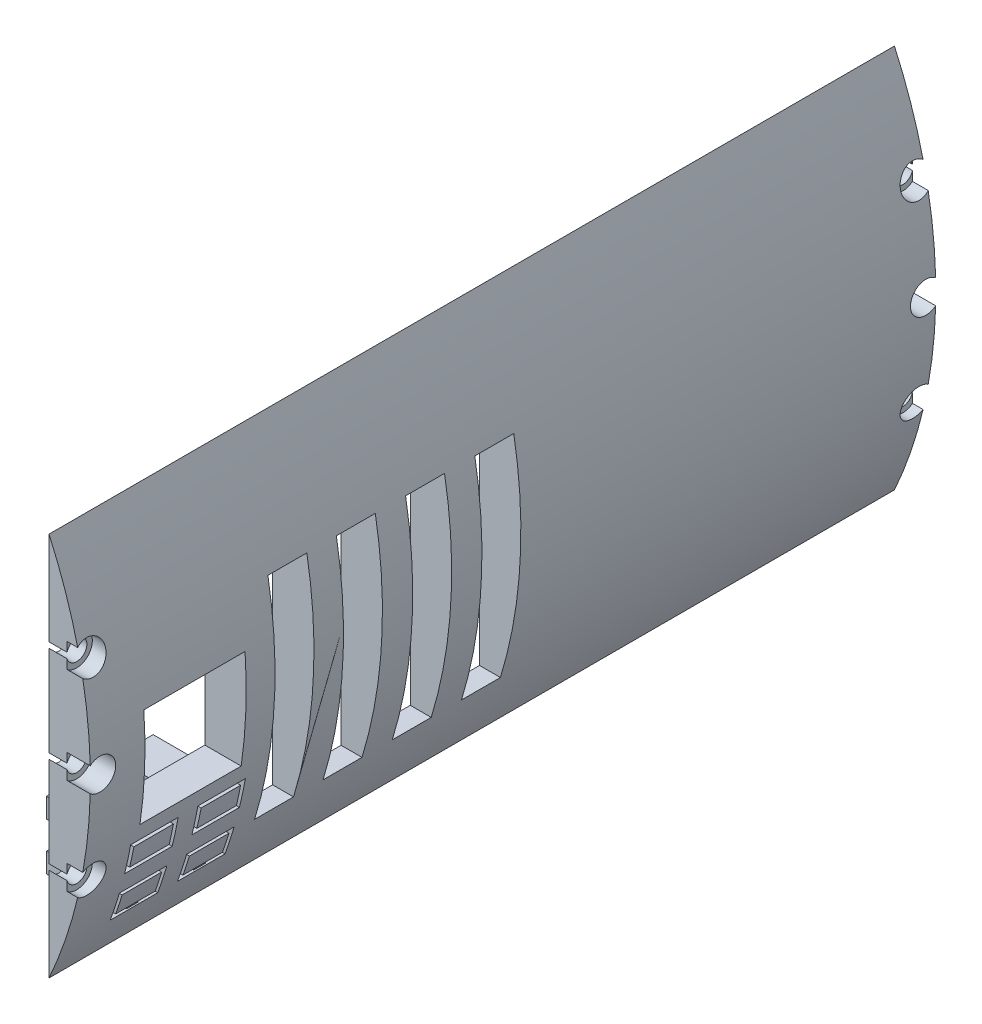
SolidWorks part; units mm, degrees
ref_plane "前视基准面" through (0, 0, 0) normal (0, 0, 1) x (1, 0, 0)
ref_plane "上视基准面" through (0, 0, 0) normal (0, 1, 0) x (1, 0, 0)
ref_plane "右视基准面" through (0, 0, 0) normal (1, 0, 0) x (0, 0, -1)
sketch "草图2" plane through (0, 0, 0) normal (0, 0, 1) x (1, 0, 0)
  line L0 (-18.6863, -24.6863) -> (-18.6863, 24.6863)
  line L1 (-18.6863, 24.6863) -> (-20.6863, 22.5)
  line L2 (-20.6863, 22.5) -> (-20.6863, -22.5)
  line L3 (-20.6863, -22.5) -> (-18.6863, -24.6863)
  line L4 (13.6863, 22.979) -> (24.6863, 22.979)
  line L5 (17.2863, 22.979) -> (17.2863, -23.106)
  line L6 (13.6863, -23.106) -> (24.6863, -23.106)
  line L7 (20.6863, -23.106) -> (20.6863, 22.979)
  line L8 (24.6863, 24.6863) -> (24.6863, -24.6863) construction
  line L9 (-13.496, 11.8369) -> (-13.496, 12.8619) construction
  line L10 (-7.5848, 7.122) -> (-8.6028, 7.122) construction
  line L11 (-8.6869, 9.122) -> (-7.6512, 9.122) construction
  line L12 (-13.496, -16.9434) -> (-13.496, -15.9184) construction
  line L13 (2.6789, -10.6646) -> (3.73, -10.6646) construction
  line L14 (6.5171, -16.946) -> (6.5171, -15.9216) construction
  line L15 (-8.7583, -10.6646) -> (-7.7073, -10.6646) construction
  line L16 (-13.496, 3.0566) -> (-13.496, 4.0816) construction
  line L17 (-11.496, 4.091) -> (-11.496, 3.064) construction
  line L18 (-11.496, -7.1455) -> (-11.496, -8.1725) construction
  line L19 (6.5171, 11.8402) -> (6.5171, 12.8645) construction
  line L20 (3.5348, -12.6646) -> (2.5249, -12.6646) construction
  line L21 (-11.496, -15.909) -> (-11.496, -16.936) construction
  line L22 (11.6863, -25.106) -> (18.0922, -25.106) construction
  line L23 (8.5171, -15.9055) -> (8.5171, -16.9332) construction
  line L24 (-11.496, 12.8545) -> (-11.496, 11.8275) construction
  line L25 (8.5171, 12.8518) -> (8.5171, 11.8241) construction
  line L26 (-16.6863, -25.5479) -> (-16.6863, 25.5479) construction
  line L27 (-13.496, -8.1631) -> (-13.496, -7.1381) construction
  line L28 (8.5171, -7.1482) -> (8.5171, -8.1759) construction
  line L29 (6.5171, -8.1598) -> (6.5171, -7.1355) construction
  line L30 (6.5171, 3.054) -> (6.5171, 4.0784) construction
  line L31 (3.5744, 7.122) -> (2.5564, 7.122) construction
  line L32 (8.5171, 4.0945) -> (8.5171, 3.0668) construction
  line L33 (11.6863, 24.979) -> (18.4746, 24.979) construction
  line L34 (-7.5533, -12.6646) -> (-8.5631, -12.6646) construction
  line L35 (2.6229, 9.122) -> (3.6585, 9.122) construction
  line L36 (15.2863, 24.979) -> (15.2863, -25.106) construction
  line L37 (11.6863, 24.979) -> (11.6863, -25.106) construction
  line L38 (-24.6863, -24.6863) -> (-24.6863, 24.6863) construction
  line L39 (13.6863, 22.979) -> (13.6863, -23.106) construction
  line L40 (14.6863, -4.612) -> (14.6863, -9.612) construction
  line L41 (14.6863, 13.549) -> (14.6863, 8.549) construction
  line L42 (12.6863, -6.212) -> (12.6863, -8.012) construction
  line L43 (12.6863, 11.949) -> (12.6863, 10.149) construction
  line L44 (-18.6863, -24.6863) -> (-24.6863, -24.6863) construction
  line L45 (-18.6863, 24.6863) -> (-24.6863, 24.6863) construction
  line L46 (14.6863, -13.756) -> (14.6863, -18.756) construction
  line L47 (12.6863, -15.356) -> (12.6863, -17.156) construction
  line L48 (-19.6863, 11.4431) -> (-19.6863, 13.2431) construction
  line L49 (-19.6863, 13.2431) -> (-24.6863, 13.2431) construction
  line L50 (-24.6863, 11.4431) -> (-19.6863, 11.4431) construction
  line L51 (-19.6863, -0.9) -> (-19.6863, 0.9) construction
  line L52 (-19.6863, 0.9) -> (-24.6863, 0.9) construction
  line L53 (-24.6863, -0.9) -> (-19.6863, -0.9) construction
  line L54 (-19.6863, -11.4431) -> (-24.6863, -11.4431) construction
  line L55 (-22.6863, 23.3791) -> (-22.6863, -23.3791) construction
  line L56 (-24.6863, -13.2431) -> (-19.6863, -13.2431) construction
  line L57 (-19.6863, -13.2431) -> (-19.6863, -11.4431) construction
  line L58 (19.6863, -11.4431) -> (19.6863, -13.2431) construction
  line L59 (22.6863, -13.0915) -> (19.6863, -13.0915) construction
  line L60 (19.6863, -11.5948) -> (22.6863, -11.5948) construction
  line L61 (19.6863, 13.2431) -> (19.6863, 11.4431) construction
  line L62 (22.6863, 11.5948) -> (19.6863, 11.5948) construction
  line L63 (19.6863, 13.0915) -> (22.6863, 13.0915) construction
  line L64 (22.6863, -0.7483) -> (19.6863, -0.7483) construction
  line L65 (22.6863, -23.3791) -> (22.6863, 23.3791) construction
  line L66 (19.6863, 0.7483) -> (22.6863, 0.7483) construction
  line L67 (19.6863, 0.9) -> (19.6863, -0.9) construction
  line L68 (-19.0096, -24.5333) -> (-17.553, -22.4531) construction
  line L69 (-15.0955, -24.1738) -> (-16.5521, -26.2541) construction
  line L70 (-16.5521, -26.2541) -> (-19.0096, -24.5333) construction
  line L71 (-26.2541, 16.5521) -> (-24.5333, 19.0096) construction
  line L72 (-24.5333, 19.0096) -> (-22.4531, 17.553) construction
  line L73 (-24.1738, 15.0955) -> (-26.2541, 16.5521) construction
  line L74 (24.5333, -19.0096) -> (22.4531, -17.553) construction
  line L75 (26.2541, -16.5521) -> (24.5333, -19.0096) construction
  line L76 (24.1738, -15.0955) -> (26.2541, -16.5521) construction
  line L77 (15.0955, 24.1738) -> (16.5521, 26.2541) construction
  line L78 (19.0096, 24.5333) -> (17.553, 22.4531) construction
  line L79 (16.5521, 26.2541) -> (19.0096, 24.5333) construction
  line L80 (24.6863, 13.2431) -> (19.6863, 13.2431) construction
  line L81 (19.6863, 11.4431) -> (24.6863, 11.4431) construction
  line L82 (24.6863, 0.9) -> (19.6863, 0.9) construction
  line L83 (19.6863, -0.9) -> (24.6863, -0.9) construction
  line L84 (24.6863, -11.4431) -> (19.6863, -11.4431) construction
  line L85 (19.6863, -13.2431) -> (24.6863, -13.2431) construction
  line L86 (13.6863, -9.612) -> (14.6863, -9.612) construction
  line L87 (14.6863, -4.612) -> (13.6863, -4.612) construction
  line L88 (13.6863, 8.549) -> (14.6863, 8.549) construction
  line L89 (14.6863, 13.549) -> (13.6863, 13.549) construction
  line L90 (14.6863, -6.212) -> (12.6863, -6.212) construction
  line L91 (12.6863, -8.012) -> (14.6863, -8.012) construction
  line L92 (14.6863, 11.949) -> (12.6863, 11.949) construction
  line L93 (12.6863, 10.149) -> (14.6863, 10.149) construction
  line L94 (13.6863, -18.756) -> (14.6863, -18.756) construction
  line L95 (14.6863, -13.756) -> (13.6863, -13.756) construction
  line L96 (14.6863, -15.356) -> (12.6863, -15.356) construction
  line L97 (12.6863, -17.156) -> (14.6863, -17.156) construction
  circle A0 centre (-17.526, -16.002) radius 0.9
  circle A1 centre (4.699, 11.303) radius 2
  circle A2 centre (4.699, 11.303) radius 0.9
  circle A3 centre (6.985, -21.844) radius 2
  circle A4 centre (6.985, -21.844) radius 0.9
  circle A5 centre (0, 0) radius 26.5 construction
  circle A6 centre (0, 0) radius 28.5 construction
  arc A7 (23.1707, 23.1707) -> (-23.1707, 23.1707) centre (0, -30) ccw
  arc A8 (-23.1707, 23.1707) -> (-23.1707, -23.1707) centre (30, 0) ccw
  arc A9 (23.1707, -23.1707) -> (23.1707, 23.1707) centre (-30, 0) ccw
  arc A10 (-24.6863, 24.6863) -> (-24.6863, -24.6863) centre (30, 0) ccw
  arc A11 (24.6863, 24.6863) -> (-24.6863, 24.6863) centre (0, -30) ccw
  arc A12 (-24.6863, -24.6863) -> (24.6863, -24.6863) centre (0, 30) ccw
  arc A13 (24.6863, -24.6863) -> (24.6863, 24.6863) centre (-30, 0) ccw
  arc A14 (-23.1707, -23.1707) -> (23.1707, -23.1707) centre (0, 30) ccw
  arc A15 (-18.6863, -17.631) -> (-18.6863, -14.373) centre (-17.526, -16.002) ccw
  arc A16 (3.5348, -12.6646) -> (6.5171, -15.9216) centre (7.4858, -12.0407) ccw construction
  arc A17 (8.5171, -15.9055) -> (8.5171, -8.1759) centre (7.4858, -12.0407) ccw construction
  arc A18 (6.5171, -8.1598) -> (3.73, -10.6646) centre (7.4858, -12.0407) ccw construction
  arc A19 (-11.496, -16.936) -> (-7.5533, -12.6646) centre (-12.5142, -12.0407) ccw construction
  arc A20 (3.5744, 7.122) -> (6.5171, 4.0784) centre (7.4858, 7.9593) ccw construction
  arc A21 (11.6863, -9.3285) -> (8.5171, -7.1482) centre (7.4858, -12.0407) ccw construction
  arc A22 (8.5171, -16.9332) -> (11.6863, -14.753) centre (7.4858, -12.0407) ccw construction
  arc A23 (6.5171, -7.1355) -> (2.6789, -10.6646) centre (7.4858, -12.0407) ccw construction
  arc A24 (-15.1576, -16.2848) -> (-13.496, -16.9434) centre (-12.5142, -12.0407) ccw construction
  arc A25 (-8.6869, 9.122) -> (-11.496, 11.8275) centre (-12.5142, 7.9593) ccw construction
  arc A26 (-7.6512, 9.122) -> (-11.496, 12.8545) centre (-12.5142, 7.9593) ccw construction
  arc A27 (-11.496, -15.909) -> (-8.5631, -12.6646) centre (-12.5142, -12.0407) ccw construction
  arc A28 (-13.496, -7.1381) -> (-15.1576, -7.7966) centre (-12.5142, -12.0407) ccw construction
  arc A29 (-13.496, -8.1631) -> (-13.496, -15.9184) centre (-12.5142, -12.0407) ccw construction
  arc A30 (8.5171, 4.0945) -> (8.5171, 11.8241) centre (7.4858, 7.9593) ccw construction
  arc A31 (6.5171, 11.8402) -> (3.6585, 9.122) centre (7.4858, 7.9593) ccw construction
  arc A32 (11.6863, 10.6715) -> (8.5171, 12.8518) centre (7.4858, 7.9593) ccw construction
  arc A33 (-11.496, 4.091) -> (-8.6028, 7.122) centre (-12.5142, 7.9593) ccw construction
  arc A34 (-13.496, 12.8619) -> (-15.1576, 12.2034) centre (-12.5142, 7.9593) ccw construction
  arc A35 (-8.7583, -10.6646) -> (-11.496, -8.1725) centre (-12.5142, -12.0407) ccw construction
  arc A36 (-11.496, 3.064) -> (-7.5848, 7.122) centre (-12.5142, 7.9593) ccw construction
  arc A37 (-7.7073, -10.6646) -> (-11.496, -7.1455) centre (-12.5142, -12.0407) ccw construction
  arc A38 (2.5249, -12.6646) -> (6.5171, -16.946) centre (7.4858, -12.0407) ccw construction
  arc A39 (6.5171, 12.8645) -> (2.6229, 9.122) centre (7.4858, 7.9593) ccw construction
  arc A40 (8.5171, 3.0668) -> (11.6863, 5.247) centre (7.4858, 7.9593) ccw construction
  arc A41 (-15.1576, 3.7152) -> (-13.496, 3.0566) centre (-12.5142, 7.9593) ccw construction
  arc A42 (-13.496, 11.8369) -> (-13.496, 4.0816) centre (-12.5142, 7.9593) ccw construction
  arc A43 (2.5564, 7.122) -> (6.5171, 3.054) centre (7.4858, 7.9593) ccw construction
  arc A44 (-16.6863, -6.9478) -> (-15.1576, -7.7966) centre (-15.6863, -6.9478) ccw construction
  arc A45 (-15.1576, 3.7152) -> (-16.6863, 2.8664) centre (-15.6863, 2.8664) ccw construction
  arc A46 (-15.1576, -16.2848) -> (-16.6863, -17.1336) centre (-15.6863, -17.1336) ccw construction
  arc A47 (-16.6863, 13.0522) -> (-15.1576, 12.2034) centre (-15.6863, 13.0522) ccw construction
  arc A48 (11.6863, -17.1159) -> (10.1529, -16.27) centre (10.6863, -17.1159) ccw construction
  arc A49 (10.1529, -7.8114) -> (11.6863, -6.9656) centre (10.6863, -6.9656) ccw construction
  arc A50 (11.6863, 2.8841) -> (10.1529, 3.73) centre (10.6863, 2.8841) ccw construction
  arc A51 (10.1529, 12.1886) -> (11.6863, 13.0344) centre (10.6863, 13.0344) ccw construction
sketch "草图3" plane through (0, 0, 0) normal (0, 0, 1) x (1, 0, 0)
  line L2 (24.6863, 24.6863) -> (24.6863, -24.6863)
  line L3 (24.6863, 24.6863) -> (24.6863, -24.6863)
  arc A3 (24.6863, -24.6863) -> (24.6863, 24.6863) centre (-30, 0) ccw
  arc A4 (24.6863, -24.6863) -> (24.6863, 24.6863) centre (-30, 0) ccw
  dimension "D1" = 0
extrude "凸台-拉伸1" add sketch "草图3" along normal blind 108.58
sketch "草图4" plane through (24.6863, 0, 0) normal (-1, 0, 0) x (0, 0, 1)
  point P0 (0, 0.001)
  point P1 (0.001, 0.001)
  point P2 (0.001, 0)
sketch "草图8" plane through (24.6863, 0, 0) normal (-1, 0, 0) x (0, 0, 1)
  line L0 (108.58, 24.6863) -> (108.58, -24.6863) construction
  line L1 (108.58, 24.6863) -> (0, 24.6863) construction
  line B0 (108.83, -24.6863) -> (108.83, 24.6863)
  line B1 (120.832, 24.6863) -> (-9.168, 24.6863)
  line B2 (2.754, 23.106) -> (2.754, -22.979)
  line B3 (2.754, -22.979) -> (104.83, -22.979)
  line B4 (104.83, 23.106) -> (2.754, 23.106)
  line B5 (104.83, -22.979) -> (104.83, 23.106)
  circle B6 centre (107.33, 12.3431) radius 0.9
  line B7 (120.832, 30) -> (-9.168, 30)
  circle B8 centre (17.454, 16.256) radius 2.5
  circle B9 centre (1.254, 12.3431) radius 0.9
  line B10 (-0.246, 24.6863) -> (-0.246, -24.6863)
  line B11 (-9.168, -30) -> (-9.168, 30)
  line B12 (-19.168, -28.5) -> (-19.168, 28.5)
  circle B13 centre (1.254, 0) radius 0.9
  circle B14 centre (1.254, -12.3431) radius 0.9
  line B15 (120.832, -30) -> (120.832, 30)
  circle B16 centre (102.036, 7.112) radius 2.5
  circle B17 centre (107.33, 0) radius 0.9
  circle B18 centre (102.036, -11.049) radius 2.5
  circle B19 centre (102.036, -11.049) radius 0.9
  circle B20 centre (107.33, -12.3431) radius 0.9
  circle B21 centre (17.454, 16.256) radius 0.9
  line B22 (-14.168, 15.0955) -> (-14.168, 19.0096)
  line B23 (-14.168, 16.5521) -> (-17.168, 16.5521)
  line B24 (-9.168, -30) -> (120.832, -30)
  line B25 (-9.168, -24.6863) -> (120.832, -24.6863)
  line B26 (-17.168, 15.0955) -> (-17.168, 19.0096)
  line B27 (-17.168, -22.4531) -> (-14.168, -22.4531)
  line B28 (-17.168, -26.2541) -> (-17.168, -22.4531)
  line B29 (-19.168, -28.5) -> (-9.168, -28.5)
  dimension "D1" = 0.25
sketch_block_instance "块1-2"
sketch_block "块1"
ref_plane "基准面5" through (30, 0, 0) normal (1, 0, 0) x (0, 0, -1)
sketch "草图11" plane through (30, 0, 0) normal (1, 0, 0) x (0, 0, -1)
  circle A0 centre (-1.254, -12.3431) radius 2
  circle A1 centre (-1.254, 0) radius 2
  circle A2 centre (-1.254, 12.3431) radius 2
  circle A3 centre (-107.33, -12.3431) radius 2
  circle A4 centre (-107.33, 0) radius 2
  circle A5 centre (-107.33, 12.3431) radius 2
  dimension "D1" = 4
extrude "切除-拉伸4" cut sketch "草图11" against normal blind 3
sketch "草图12" plane through (27, 0, 0) normal (1, 0, 0) x (0, 0, -1)
  circle A0 centre (-1.254, -12.3431) radius 1.3
  circle A1 centre (-1.254, 0) radius 1.3
  circle A2 centre (-1.254, 12.3431) radius 1.3
  circle A3 centre (-107.33, 12.3431) radius 1.3
  circle A4 centre (-107.33, 0) radius 1.3
  circle A5 centre (-107.33, -12.3431) radius 1.3
  dimension "D1" = 2.6
extrude "切除-拉伸5" cut sketch "草图12" against normal blind 14
sketch "草图14" plane through (0, 0, 0) normal (1, 0, 0) x (0, 0, -1)
  arc A0 (-108.58, -12.7002) -> (-108.58, -11.9861) centre (-107.33, -12.3431) ccw construction
  arc A1 (0, 12.6859) -> (0, 12.0004) centre (-1.254, 12.3431) ccw construction
  line B0 (-77.5411, 13.97) -> (-77.5411, -21.082) construction
  line B1 (-105.83, 23.106) -> (-105.83, -22.979)
  circle B2 centre (-97.5669, 3.9639) radius 1.2754 construction
  line B3 (-84.907, -13.8431) -> (-84.907, 6.6039) construction
  line B4 (-71.064, 6.6039) -> (-71.064, -13.8431) construction
  line B5 (12.248, 24.6863) -> (-117.752, 24.6863)
  circle B6 centre (-53.8241, 13.1941) radius 0.8163 construction
  circle B7 centre (-57.824, 13.1938) radius 1.2754 construction
  circle B8 centre (-62.714, 13.1938) radius 1.2754 construction
  line B9 (-78.367, -21.082) -> (-78.367, 13.97) construction
  line B10 (-102.56, 11.43) -> (-102.56, 21.59) construction
  line B11 (-87.699, -14.373) -> (-93.799, -14.373) construction
  line B12 (-86.3041, 13.97) -> (-86.3041, -21.082) construction
  line B13 (-79.9541, -11.176) -> (-84.7801, -11.176) construction
  line B14 (-79.827, -13.8431) -> (-84.907, -13.8431) construction
  line B15 (-84.7801, -8.636) -> (-79.9541, -8.636) construction
  line B16 (-79.827, 6.6039) -> (-79.827, -13.8431) construction
  line B17 (-76.144, -13.8431) -> (-76.144, 6.6039) construction
  line B18 (-60.714, -21.082) -> (-60.714, 13.97) construction
  line B19 (-47.3406, -2.1709) -> (-46.0194, -2.1709) construction
  line B20 (-85.161, 20.955) -> (-85.161, 15.875) construction
  line B21 (-85.161, 15.875) -> (-87.6756, 15.875) construction
  circle B22 centre (-92.567, 3.964) radius 0.7653 construction
  circle B23 centre (-95.0667, -2.286) radius 5.9146 construction
  line B24 (-99.0268, 3.714) -> (-101.067, 3.714) construction
  circle B25 centre (-90.5669, -2.286) radius 0.95 construction
  line B26 (-89.067, -5.4368) -> (-89.067, 3.714) construction
  circle B27 centre (-100.1419, 1.5138) radius 0.9254 construction
  circle B28 centre (-100.142, 1.514) radius 0.6169 construction
  circle B29 centre (-89.992, -6.086) radius 0.6169 construction
  line B30 (-89.067, -8.286) -> (-89.067, -6.7352) construction
  circle B31 centre (-84.367, 13.1938) radius 1.2754 construction
  circle B32 centre (-84.367, 13.1941) radius 0.8163 construction
  line B33 (-117.752, -30) -> (-117.752, 30)
  line B34 (-84.907, 6.6039) -> (-79.827, 6.6039) construction
  line B35 (-69.604, -21.082) -> (-69.604, 13.97) construction
  line B36 (-67.254, -13.8431) -> (-67.254, 6.6039) construction
  line B37 (-62.174, 6.6039) -> (-62.174, -13.8431) construction
  circle B38 centre (-55.697, 5.207) radius 0.3048 construction
  line B39 (-58.364, 6.6039) -> (-53.284, 6.6039) construction
  line B40 (-51.824, -21.082) -> (-51.824, 13.97) construction
  line B41 (-53.284, 6.6039) -> (-53.284, -13.8431) construction
  line B42 (-53.4111, -11.176) -> (-58.2371, -11.176) construction
  line B43 (-68.6511, 13.97) -> (-68.6511, -21.082) construction
  line B44 (-93.289, -11.303) -> (-88.209, -11.303) construction
  line B45 (-87.699, -10.773) -> (-93.799, -10.773) construction
  circle B46 centre (-97.5669, -8.5362) radius 1.2754 construction
  line B47 (-100.782, -11.938) -> (-98.115, -11.938) construction
  line B48 (-101.925, -11.8419) -> (-101.925, -11.303) construction
  line B49 (-98.115, -13.208) -> (-100.782, -13.208) construction
  line B50 (-96.845, -13.843) -> (-101.925, -13.843) construction
  line B51 (-93.289, -11.8419) -> (-93.289, -11.303) construction
  line B52 (-92.146, -11.938) -> (-89.479, -11.938) construction
  line B53 (-89.479, -11.938) -> (-89.479, -13.208) construction
  line B54 (-88.209, -13.843) -> (-93.289, -13.843) construction
  line B55 (-87.699, -16.869) -> (-93.799, -16.869) construction
  line B56 (-96.335, -20.469) -> (-96.335, -19.4001) construction
  line B57 (-98.115, -19.304) -> (-100.782, -19.304) construction
  line B58 (-100.782, -18.034) -> (-98.115, -18.034) construction
  line B59 (-101.925, -17.399) -> (-96.845, -17.399) construction
  line B60 (-93.289, -17.399) -> (-88.209, -17.399) construction
  line B61 (-89.479, -19.304) -> (-92.146, -19.304) construction
  line B62 (-88.209, -19.939) -> (-93.289, -19.939) construction
  line B63 (-87.699, -20.469) -> (-93.799, -20.469) construction
  line B64 (-96.335, -10.773) -> (-102.435, -10.773) construction
  line B65 (-103.83, -22.479) -> (-103.83, 22.606) construction
  circle B66 centre (-46.172, -18.796) radius 3.1496 construction
  line B67 (-117.752, -24.6863) -> (12.248, -24.6863)
  line B68 (-117.752, -30) -> (12.248, -30)
  line B69 (-87.2944, -8.1161) -> (-88.6156, -8.1161) construction
  line B70 (-88.2908, -8.6104) -> (-87.3319, -8.6104) construction
  circle B71 centre (-87.9636, -9.271) radius 0.3048 construction
  circle B72 centre (-97.567, 3.964) radius 0.75 construction
  line B73 (-101.067, 0.8648) -> (-101.067, -8.286) construction
  spline B74 degree 3 poles (-108.83, -1.3229) (-108.9908, -1.1406) (-109.1152, -0.9337) (-109.2436, -0.5939) (-109.2757, -0.4783) (-109.3189, -0.2424) (-109.33, -0.121) (-109.33, 0.1204) (-109.3192, 0.2398) (-109.2762, 0.476) (-109.2436, 0.5939) (-109.116, 0.9318) (-108.9908, 1.1406) (-108.83, 1.3229) knots 0 0 0 0 0.25 0.25 0.375 0.375 0.5 0.5 0.625 0.625 0.75 0.75 1 1 1 1
  line B75 (-108.83, 24.6863) -> (-108.83, -24.6863)
  line B76 (-71.064, -13.8431) -> (-76.144, -13.8431) construction
  circle B77 centre (-80.367, 13.1938) radius 1.2754 construction
  circle B78 centre (-98.75, 12.7) radius 0.8128 construction
  line B79 (-51.824, 13.97) -> (-59.7611, 13.97) construction
  circle B80 centre (-53.824, 13.1938) radius 1.2754 construction
  circle B81 centre (-91.13, 16.256) radius 1.5999 construction
  line B82 (-59.7611, 13.97) -> (-59.7611, -21.082) construction
  circle B83 centre (-71.604, 13.1938) radius 1.2754 construction
  circle B84 centre (-75.604, 13.1938) radius 1.2754 construction
  line B85 (-100.02, 11.43) -> (-100.02, 19.685) construction
  circle B86 centre (-101.29, 15.24) radius 0.8128 construction
  circle B87 centre (-101.29, 12.7) radius 0.4588 construction
  circle B88 centre (-80.3671, 13.1941) radius 0.8163 construction
  line B89 (-78.367, 13.97) -> (-86.3041, 13.97) construction
  line B90 (-105.83, -22.979) -> (-3.754, -22.979)
  line B91 (-3.754, -22.479) -> (-103.754, -22.479) construction
  line B92 (-78.367, -21.082) -> (-86.367, -21.082) construction
  circle B93 centre (-84.145, -14.351) radius 0.3048 construction
  line B94 (-127.752, -28.5) -> (-127.752, 28.5)
  line B95 (-71.1911, -11.176) -> (-76.0171, -11.176) construction
  line B96 (-69.604, 13.97) -> (-77.5411, 13.97) construction
  circle B97 centre (-66.714, 13.1938) radius 1.2754 construction
  line B98 (-60.714, 13.97) -> (-68.6511, 13.97) construction
  circle B99 centre (-97.567, 3.964) radius 0.7653 construction
  line B100 (-58.364, -13.8431) -> (-58.364, 6.6039) construction
  line B101 (-57.983, 15.367) -> (-57.983, 21.367) construction
  line B102 (-57.983, 15.367) -> (-52.903, 15.367) construction
  circle B103 centre (-55.697, 18.367) radius 0.9 construction
  line B104 (-50.3972, 9.4917) -> (-44.9948, 9.4917) construction
  circle B105 centre (-40.965, 5.334) radius 0.3048 construction
  circle B106 centre (-87.193, -14.351) radius 0.3048 construction
  line B107 (-62.3011, -11.176) -> (-67.1271, -11.176) construction
  circle B108 centre (-84.367, -20.3062) radius 0.8163 construction
  line B109 (-96.335, -14.373) -> (-102.435, -14.373) construction
  line B110 (-100.782, -13.208) -> (-100.782, -11.938) construction
  circle B111 centre (-107.33, -12.3431) radius 0.9
  line B112 (-96.335, -16.869) -> (-102.435, -16.869) construction
  line B113 (-101.925, -11.303) -> (-96.845, -11.303) construction
  line B114 (-102.435, -11.8419) -> (-102.435, -10.773) construction
  line B115 (-96.335, -14.373) -> (-96.335, -13.3041) construction
  line B116 (-102.435, -17.9379) -> (-102.435, -16.869) construction
  line B117 (-96.335, -20.469) -> (-102.435, -20.469) construction
  line B118 (-101.925, -17.9379) -> (-101.925, -17.399) construction
  line B119 (-96.845, -19.939) -> (-101.925, -19.939) construction
  line B120 (-92.146, -19.304) -> (-92.146, -18.034) construction
  line B121 (-100.782, -19.304) -> (-100.782, -18.034) construction
  circle B122 centre (-92.5669, -8.5362) radius 1.25 construction
  spline B123 degree 3 poles (-108.83, -13.666) (-108.9914, -13.4831) (-109.1153, -13.2765) (-109.2862, -12.8243) (-109.3297, -12.587) (-109.3302, -12.2254) (-109.3195, -12.1063) (-109.277, -11.8705) (-109.2447, -11.7528) (-109.1172, -11.4135) (-108.9922, -11.2042) (-108.83, -11.0203) knots 0 0 0 0 0.25 0.25 0.5 0.5 0.625 0.625 0.75 0.75 1 1 1 1
  circle B124 centre (-92.567, -8.536) radius 0.7653 construction
  circle B125 centre (-97.567, -8.536) radius 0.7653 construction
  line B126 (-89.479, -18.034) -> (-89.479, -19.304) construction
  line B127 (-92.146, -18.034) -> (-89.479, -18.034) construction
  line B128 (-89.479, -13.208) -> (-92.146, -13.208) construction
  line B129 (-98.115, -11.938) -> (-98.115, -13.208) construction
  line B130 (-93.799, -20.469) -> (-93.799, -19.4001) construction
  line B131 (-98.115, -18.034) -> (-98.115, -19.304) construction
  line B132 (-60.714, -21.082) -> (-68.714, -21.082) construction
  circle B133 centre (-66.714, -20.3062) radius 0.8163 construction
  circle B134 centre (-92.5669, -8.5362) radius 1.2754 construction
  line B135 (-92.146, -13.208) -> (-92.146, -11.938) construction
sketch_block_instance "块2-1"
sketch_block "块2"
sketch "草图15" plane through (24.6863, 0, 0) normal (-1, 0, 0) x (0, 0, 1)
  line L0 (95.0667, -2.286) -> (101.5667, -2.286) construction
  line L37 (101.5667, 4.214) -> (88.5667, 4.214)
  line L38 (101.5667, 4.214) -> (101.5667, -8.786)
  line L39 (101.5667, -8.786) -> (88.5667, -8.786)
  line L40 (88.5667, 4.214) -> (88.5667, -8.786)
  line L41 (82.3355, 13.97) -> (82.367, 10.4441) construction
  line L42 (95.0667, -2.286) -> (95.0667, 4.214) construction
  line L47 (84.867, 10.4441) -> (79.867, 10.4441)
  line L48 (84.867, 10.4441) -> (84.867, -17.5559)
  line L49 (84.867, -17.5559) -> (79.867, -17.5559)
  line L50 (79.867, 10.4441) -> (79.867, -17.5559)
  line L51 (78.367, 13.97) -> (86.3041, 13.97) construction
  line L52 (82.367, -17.5559) -> (82.367, -21.082) construction
  line L53 (78.367, -21.082) -> (86.367, -21.082) construction
  line L54 (73.5725, 13.97) -> (73.5725, 10.4439) construction
  line L55 (76.0725, 10.4439) -> (71.0725, 10.4439)
  line L56 (76.0725, 10.4439) -> (76.0725, -17.5561)
  line L57 (76.0725, -17.5561) -> (71.0725, -17.5561)
  line L58 (71.0725, 10.4439) -> (71.0725, -17.5561)
  line L59 (67.1825, 10.4441) -> (62.1825, 10.4441)
  line L60 (67.1825, 10.4441) -> (67.1825, -17.5559)
  line L61 (67.1825, -17.5559) -> (62.1825, -17.5559)
  line L62 (62.1825, 10.4441) -> (62.1825, -17.5559)
  line L63 (58.2925, 10.4355) -> (53.2925, 10.4355)
  line L64 (58.2925, 10.4355) -> (58.2925, -17.5645)
  line L65 (58.2925, -17.5645) -> (53.2925, -17.5645)
  line L66 (53.2925, 10.4355) -> (53.2925, -17.5645)
  line L67 (69.604, 13.97) -> (77.5411, 13.97) construction
  line L68 (64.6825, 13.97) -> (64.6825, 10.4441) construction
  line L69 (60.714, 13.97) -> (68.6511, 13.97) construction
  line L70 (55.7925, 13.97) -> (55.7925, 10.4355) construction
  line L71 (51.824, 13.97) -> (59.7611, 13.97) construction
  dimension "D1" = 13
  dimension "D2" = 13
  dimension "D3" = 5
  dimension "D4" = 28
extrude "切除-拉伸6" cut sketch "草图15" against normal blind 10
sketch "草图16" plane through (24.6863, 0, 0) normal (-1, 0, 0) x (0, 0, 1)
  line L0 (100.135, -10.773) -> (100.135, -11.303)
  line L1 (102.435, -10.773) -> (100.135, -10.773)
  line L2 (102.435, -10.773) -> (102.435, -14.373)
  line L3 (102.435, -14.373) -> (100.135, -14.373)
  line L4 (96.335, -10.773) -> (96.335, -14.373)
  line L5 (101.925, -11.303) -> (100.135, -11.303)
  line L6 (101.925, -11.303) -> (101.925, -13.843)
  line L7 (101.925, -13.843) -> (100.135, -13.843)
  line L8 (96.845, -11.303) -> (96.845, -13.843)
  line L9 (102.435, -16.869) -> (100.135, -16.869)
  line L10 (102.435, -16.869) -> (102.435, -20.469)
  line L11 (102.435, -20.469) -> (100.135, -20.469)
  line L12 (96.335, -16.869) -> (96.335, -20.469)
  line L13 (101.925, -17.399) -> (100.135, -17.399)
  line L14 (101.925, -17.399) -> (101.925, -19.939)
  line L15 (101.925, -19.939) -> (100.135, -19.939)
  line L16 (96.845, -17.399) -> (96.845, -19.939)
  line L17 (93.799, -10.773) -> (91.499, -10.773)
  line L18 (93.799, -10.773) -> (93.799, -14.373)
  line L19 (93.799, -14.373) -> (91.499, -14.373)
  line L20 (87.699, -10.773) -> (87.699, -14.373)
  line L21 (93.799, -16.869) -> (91.499, -16.869)
  line L22 (93.799, -16.869) -> (93.799, -20.469)
  line L23 (93.799, -20.469) -> (91.499, -20.469)
  line L24 (87.699, -16.869) -> (87.699, -20.469)
  line L25 (93.289, -17.399) -> (91.499, -17.399)
  line L26 (93.289, -17.399) -> (93.289, -19.939)
  line L27 (93.289, -19.939) -> (91.499, -19.939)
  line L28 (88.209, -17.399) -> (88.209, -19.939)
  line L29 (93.289, -11.303) -> (91.499, -11.303)
  line L30 (93.289, -11.303) -> (93.289, -13.843)
  line L31 (93.289, -13.843) -> (91.499, -13.843)
  line L32 (88.209, -11.303) -> (88.209, -13.843)
  line L33 (98.635, -10.773) -> (98.635, -11.303)
  line L34 (100.135, -11.038) -> (99.385, -11.303) construction
  line L35 (99.385, -11.303) -> (98.635, -11.038) construction
  line L36 (100.135, -13.843) -> (100.135, -14.373)
  line L37 (98.635, -13.843) -> (98.635, -14.373)
  line L38 (100.135, -16.869) -> (100.135, -17.399)
  line L39 (98.635, -16.869) -> (98.635, -17.399)
  line L40 (100.135, -19.939) -> (100.135, -20.469)
  line L41 (98.635, -19.939) -> (98.635, -20.469)
  line L42 (91.499, -10.773) -> (91.499, -11.303)
  line L43 (89.999, -10.773) -> (89.999, -11.303)
  line L44 (91.499, -11.038) -> (90.749, -11.303) construction
  line L45 (90.749, -11.303) -> (89.999, -11.038) construction
  line L46 (91.499, -13.843) -> (91.499, -14.373)
  line L47 (89.999, -13.843) -> (89.999, -14.373)
  line L48 (91.499, -16.869) -> (91.499, -17.399)
  line L49 (89.999, -16.869) -> (89.999, -17.399)
  line L50 (91.499, -19.939) -> (91.499, -20.469)
  line L51 (89.999, -19.939) -> (89.999, -20.469)
  line L52 (98.635, -14.373) -> (96.335, -14.373)
  line L53 (98.635, -13.843) -> (96.845, -13.843)
  line L54 (98.635, -10.773) -> (96.335, -10.773)
  line L55 (98.635, -11.303) -> (96.845, -11.303)
  line L56 (98.635, -17.399) -> (96.845, -17.399)
  line L57 (98.635, -19.939) -> (96.845, -19.939)
  line L58 (98.635, -20.469) -> (96.335, -20.469)
  line L59 (89.999, -20.469) -> (87.699, -20.469)
  line L60 (89.999, -19.939) -> (88.209, -19.939)
  line L61 (89.999, -17.399) -> (88.209, -17.399)
  line L62 (89.999, -16.869) -> (87.699, -16.869)
  line L63 (89.999, -14.373) -> (87.699, -14.373)
  line L64 (89.999, -13.843) -> (88.209, -13.843)
  line L65 (89.999, -11.303) -> (88.209, -11.303)
  line L66 (89.999, -10.773) -> (87.699, -10.773)
  line L67 (98.635, -16.869) -> (96.335, -16.869)
  dimension "D1" = 1.5
  dimension "D2" = 1.5
extrude "切除-拉伸7" cut sketch "草图16" against normal blind 10
ref_plane "基准面7" through (30, 0, 0) normal (1, 0, 0) x (0, 0, -1)
sketch "草图17" plane through (30, 0, 0) normal (1, 0, 0) x (0, 0, -1)
  line L1 (-100.135, -10.773) -> (-98.635, -10.773)
  line L2 (-100.135, -10.773) -> (-100.135, -11.303)
  line L3 (-100.135, -11.303) -> (-98.635, -11.303)
  line L4 (-98.635, -10.773) -> (-98.635, -11.303)
  line L5 (-100.135, -13.843) -> (-98.635, -13.843)
  line L6 (-100.135, -13.843) -> (-100.135, -14.373)
  line L7 (-100.135, -14.373) -> (-98.635, -14.373)
  line L8 (-98.635, -13.843) -> (-98.635, -14.373)
  line L9 (-100.135, -16.869) -> (-98.635, -16.869)
  line L10 (-100.135, -16.869) -> (-100.135, -17.399)
  line L11 (-100.135, -17.399) -> (-98.635, -17.399)
  line L12 (-98.635, -16.869) -> (-98.635, -17.399)
  line L13 (-100.135, -19.939) -> (-98.635, -19.939)
  line L14 (-100.135, -19.939) -> (-100.135, -20.469)
  line L15 (-100.135, -20.469) -> (-98.635, -20.469)
  line L16 (-98.635, -19.939) -> (-98.635, -20.469)
  line L17 (-91.499, -16.869) -> (-89.999, -16.869)
  line L18 (-91.499, -16.869) -> (-91.499, -17.399)
  line L19 (-91.499, -17.399) -> (-89.999, -17.399)
  line L20 (-89.999, -16.869) -> (-89.999, -17.399)
  line L21 (-91.499, -19.939) -> (-89.999, -19.939)
  line L22 (-91.499, -19.939) -> (-91.499, -20.469)
  line L23 (-91.499, -20.469) -> (-89.999, -20.469)
  line L24 (-89.999, -19.939) -> (-89.999, -20.469)
  line L25 (-91.499, -10.773) -> (-89.999, -10.773)
  line L26 (-91.499, -10.773) -> (-91.499, -11.303)
  line L27 (-91.499, -11.303) -> (-89.999, -11.303)
  line L28 (-89.999, -10.773) -> (-89.999, -11.303)
  line L29 (-91.499, -13.843) -> (-89.999, -13.843)
  line L30 (-91.499, -13.843) -> (-91.499, -14.373)
  line L31 (-91.499, -14.373) -> (-89.999, -14.373)
  line L32 (-89.999, -13.843) -> (-89.999, -14.373)
extrude "切除-拉伸8" cut sketch "草图17" against normal offset from surface (3.8137 mm away) 1.5 up to face at (24.6863, -12.573, 92.5215)
sketch "草图18" plane through (24.6863, 0, 0) normal (-1, 0, 0) x (0, 0, 1)
  line L1 (88.209, -11.303) -> (93.289, -11.303)
  line L2 (88.209, -11.303) -> (88.209, -13.843)
  line L3 (88.209, -13.843) -> (93.289, -13.843)
  line L4 (93.289, -11.303) -> (93.289, -13.843)
  line L5 (88.209, -17.399) -> (93.289, -17.399)
  line L6 (88.209, -17.399) -> (88.209, -19.939)
  line L7 (88.209, -19.939) -> (93.289, -19.939)
  line L8 (93.289, -17.399) -> (93.289, -19.939)
  line L9 (96.845, -11.303) -> (101.925, -11.303)
  line L10 (96.845, -11.303) -> (96.845, -13.843)
  line L11 (96.845, -13.843) -> (101.925, -13.843)
  line L12 (101.925, -11.303) -> (101.925, -13.843)
  line L13 (96.845, -17.399) -> (101.925, -17.399)
  line L14 (96.845, -17.399) -> (96.845, -19.939)
  line L15 (96.845, -19.939) -> (101.925, -19.939)
  line L16 (101.925, -17.399) -> (101.925, -19.939)
extrude "凸台-拉伸2" add sketch "草图18" along normal blind 7
